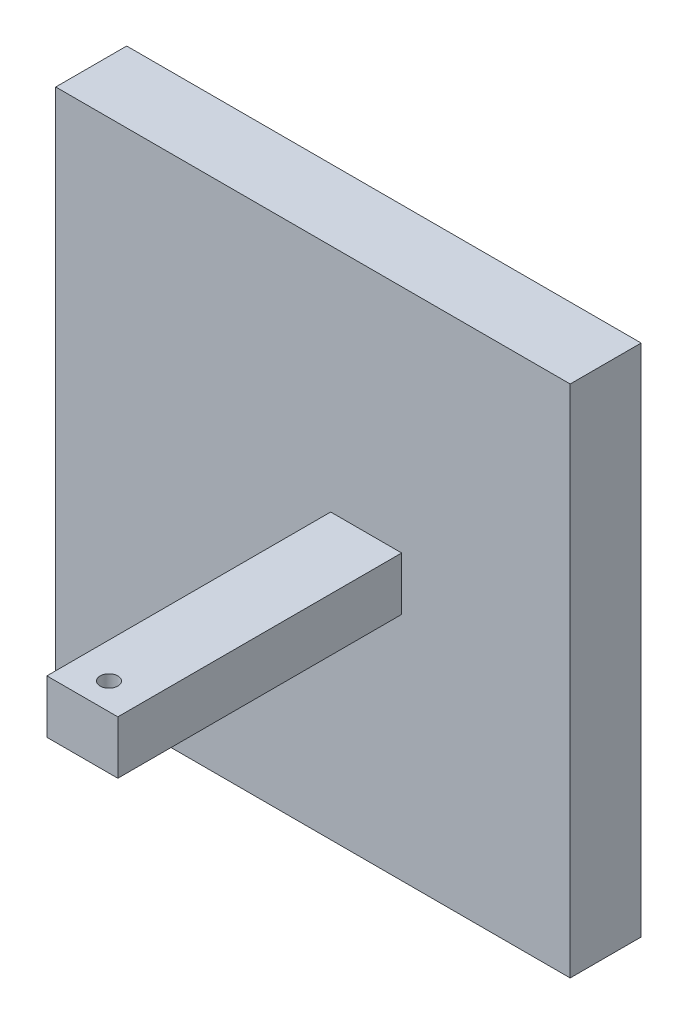
SolidWorks part; units mm, degrees
ref_plane "Front Plane" through (0, 0, 0) normal (0, 0, 1) x (1, 0, 0)
ref_plane "Top Plane" through (0, 0, 0) normal (0, 1, 0) x (1, 0, 0)
ref_plane "Right Plane" through (0, 0, 0) normal (1, 0, 0) x (0, 0, -1)
sketch "Sketch1" plane through (0, 0, 0) normal (0, 0, 1) x (1, 0, 0)
  line L1 (-368.3, 368.3) -> (368.3, 368.3)
  line L2 (-368.3, 368.3) -> (-368.3, -368.3)
  line L3 (-368.3, -368.3) -> (368.3, -368.3)
  line L4 (368.3, 368.3) -> (368.3, -368.3)
  line L5 (-368.3, 368.3) -> (368.3, -368.3) construction
  line L6 (-368.3, -368.3) -> (368.3, 368.3) construction
  point P0 (0, 0)
  dimension "D1" = 736.6
  dimension "D2" = 736.6
extrude "Boss-Extrude1" add sketch "Sketch1" along normal blind 101.6
sketch "Sketch2" plane through (0, 0, 101.6) normal (0, 0, 1) x (1, 0, 0)
  line L1 (25.4, 38.1) -> (127, 38.1)
  line L2 (25.4, 38.1) -> (25.4, -38.1)
  line L3 (25.4, -38.1) -> (127, -38.1)
  line L4 (127, 38.1) -> (127, -38.1)
  line L5 (25.4, 38.1) -> (127, -38.1) construction
  line L6 (25.4, -38.1) -> (127, 38.1) construction
  point P0 (76.2, 0)
  point P5 (0, 0)
  dimension "D1" = 76.2
  dimension "D2" = 101.6
  dimension "D3" = 76.2
extrude "Boss-Extrude2" add sketch "Sketch2" along normal blind 406.4
sketch "Sketch3" plane through (0, -38.1, 0) normal (0, -1, 0) x (-1, 0, 0)
  line L0 (-127, -508) -> (-127, -101.6) construction
  line L1 (-25.4, -508) -> (-127, -508) construction
  circle A0 centre (-76.2, -469.9) radius 12.7
  dimension "D1" = 25.4
  dimension "D2" = 50.8
  dimension "D3" = 38.1
extrude "Cut-Extrude1" cut sketch "Sketch3" against normal blind 508
